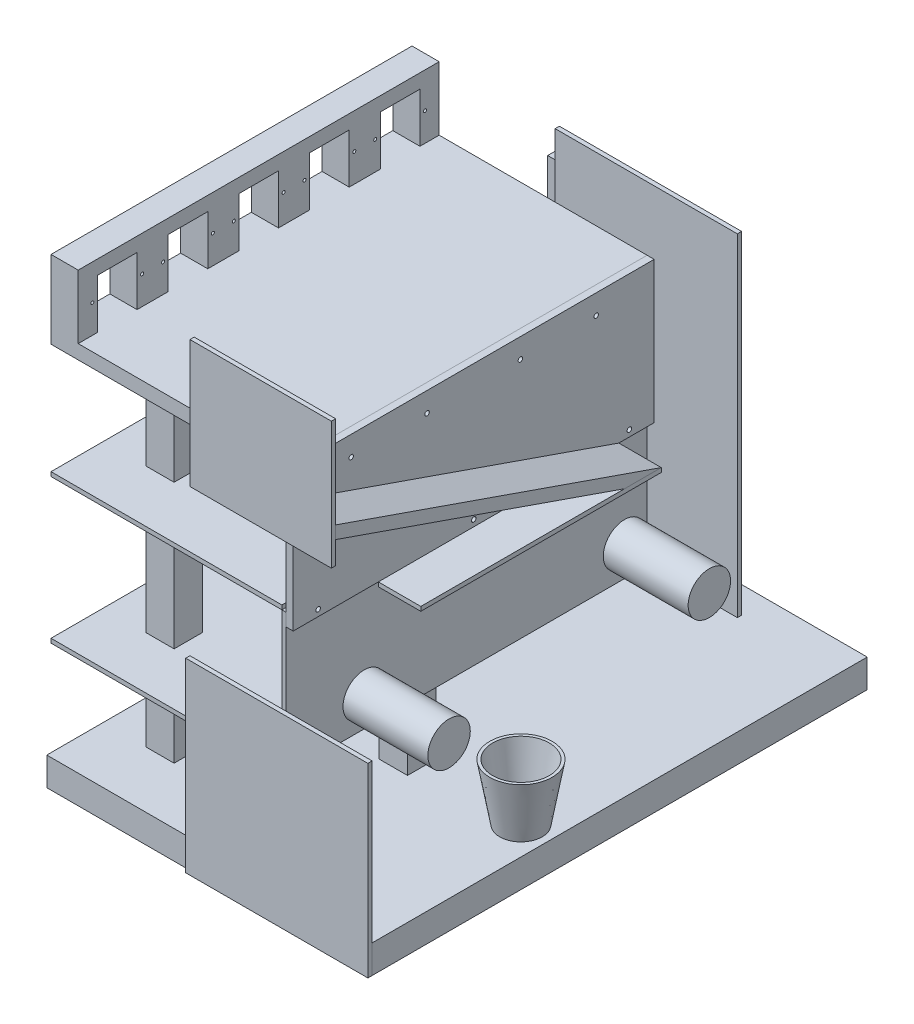
SolidWorks part; units mm, degrees
ref_plane "Front Plane" through (0, 0, 0) normal (0, 0, 1) x (1, 0, 0)
ref_plane "Top Plane" through (0, 0, 0) normal (0, 1, 0) x (1, 0, 0)
ref_plane "Right Plane" through (0, 0, 0) normal (1, 0, 0) x (0, 0, -1)
sketch "Sketch1" plane through (0, 0, 0) normal (0, 0, 1) x (1, 0, 0)
  line L0 (0, 0) -> (0, 55)
  line L1 (0, 55) -> (19.2, 55)
  line L2 (19.2, 55) -> (19.2, 10)
  line L3 (19.2, 10) -> (166.2, 10)
  line L4 (166.2, 10) -> (166.2, 0)
  line L5 (166.2, 0) -> (0, 0)
  dimension "D1" = 19.2
  dimension "D2" = 45
  dimension "D3" = 10
  dimension "D4" = 147
extrude "Boss-Extrude1" add sketch "Sketch1" along normal blind 236
sketch "Sketch2" plane through (19.2, 0, 0) normal (1, 0, 0) x (0, 0, -1)
  line L0 (-236, 10) -> (-236, 55) construction
  line L1 (-236, 10) -> (-236, 55)
  line L2 (-232.2097, 30) -> (-184.0341, 30) construction
  line L4 (-208.4, 61.6769) -> (-208.4, -8.4574) construction
  line L5 (-231.187, 27.5) -> (-166.5462, 27.5) construction
  line L6 (-236, 10) -> (0, 10) construction
  line L8 (-222.4, 45) -> (-194.4, 45)
  line L9 (-222.4, 45) -> (-222.4, 10)
  line L10 (-222.4, 10) -> (-194.4, 10)
  line L11 (-194.4, 45) -> (-194.4, 10)
  line L12 (-222.4, 45) -> (-194.4, 10) construction
  line L13 (-222.4, 10) -> (-194.4, 45) construction
  circle A0 centre (-226, 30) radius 1.075
  circle A1 centre (-190.8, 30) radius 1.075
  point P12 (-208.4, 27.5)
  dimension "D2" = 2.15
  dimension "D3" = 17.6
  dimension "D1" = 15
  dimension "D4" = 17.5
  dimension "D5" = 28
  dimension "D6" = 35
extrude "Cut-Extrude1" cut sketch "Sketch2" against normal blind 236 contours L9 L10 L11 L8 | A0 | A1
sketch "Sketch4" plane through (0, 0, 0) normal (0, 0, -1) x (-1, 0, 0)
  line L6 (-166.2, 0) -> (0, 0)
  line L7 (0, 0) -> (0, 55)
  line L8 (0, 55) -> (-19.2, 55)
  line L9 (-19.2, 55) -> (-19.2, 10)
  line L10 (-19.2, 10) -> (-166.2, 10)
  line L11 (-166.2, 10) -> (-166.2, 0)
  line L12 (-166.2, 0) -> (0, 0)
  line L13 (0, 0) -> (0, 55)
  line L14 (0, 55) -> (-19.2, 55)
  line L15 (-19.2, 55) -> (-19.2, 10)
  line L16 (-19.2, 10) -> (-166.2, 10)
  line L17 (-166.2, 10) -> (-166.2, 0)
  dimension "D1" = 0
extrude "Boss-Extrude3" add sketch "Sketch4" along normal blind 19.2
pattern_linear "LPattern2" count 5 spacing 50 along (0, 0, -1) of "Cut-Extrude1"
ref_plane "Plane8" through (0, 10, 0) normal (0, 1, 0) x (1, 0, 0)
sketch "Sketch11" plane through (0, 10, 0) normal (0, 1, 0) x (1, 0, 0)
  line L0 (166.2, -236) -> (166.2, 19.2) construction
  line L1 (166.2, -236) -> (166.2, 19.2)
  line L2 (166.2, 19.2) -> (171.2, 19.2)
  line L3 (171.2, 19.2) -> (171.2, -236)
  line L4 (171.2, -236) -> (166.2, -236)
  dimension "D1" = 5
extrude "Boss-Extrude6" add sketch "Sketch11" against normal blind 100 separate body
sketch "Sketch12" plane through (0, 0, 0) normal (0, -1, 0) x (1, 0, 0)
  line L0 (166.2, 236) -> (166.2, -19.2) construction
  line L1 (166.2, 24.8) -> (166.2, 18.8)
  line L2 (193.3393, 108.4) -> (-22.8673, 108.4) construction
  line L3 (166.2, 24.8) -> (163.2, 24.8)
  line L4 (163.2, 24.8) -> (163.2, 18.8)
  line L5 (163.2, 18.8) -> (166.2, 18.8)
  line L6 (166.2, 192) -> (163.2, 192)
  line L7 (166.2, -19.2) -> (0, -19.2) construction
  line L8 (163.2, 192) -> (163.2, 198)
  line L9 (163.2, 198) -> (166.2, 198)
  line L10 (166.2, 192) -> (166.2, 198)
  line L11 (166.2, 78.4) -> (163.2, 78.4)
  line L12 (163.2, 78.4) -> (163.2, 72.4)
  line L13 (163.2, 72.4) -> (166.2, 72.4)
  line L14 (166.2, -19.2) -> (166.2, 236) construction
  line L15 (166.2, 72.4) -> (166.2, 78.4)
  line L16 (163.2, 144.4) -> (166.2, 144.4)
  line L17 (163.2, 138.4) -> (163.2, 144.4)
  line L18 (166.2, 138.4) -> (163.2, 138.4)
  line L19 (166.2, 144.4) -> (166.2, 138.4)
  dimension "D1" = 3
  dimension "D2" = 6
  dimension "D3" = 38
  dimension "D4" = 3
  dimension "D5" = 6
  dimension "D6" = 30
extrude "Boss-Extrude7" add sketch "Sketch12" along normal blind 8
ref_plane "Plane13" through (0, 0, 108.4) normal (0, 0, 1) x (1, 0, 0)
sketch "Sketch13" plane through (163.2, 0, 0) normal (-1, 0, 0) x (0, 0, 1)
  line L0 (75.4, -8) -> (75.4, 0) construction
  line L1 (72.4, -4) -> (78.4, -4) construction
  circle A0 centre (75.4, -4) radius 1.6
extrude "Cut-Extrude2" cut sketch "Sketch13" against normal blind 70
mirror "Mirror1" about plane through (0, 0, 108.4) normal (0, 0, 1) of "Cut-Extrude2"
sketch "Sketch14" plane through (163.2, 0, 0) normal (-1, 0, 0) x (0, 0, 1)
  line L0 (21.8, -8.505) -> (21.8, 0.2869) construction
  line L1 (18.8, -4) -> (24.8, -4) construction
  circle A0 centre (21.8, -4) radius 1.6
extrude "Cut-Extrude4" cut sketch "Sketch14" against normal blind 70
mirror "Mirror2" about plane through (0, 0, 108.4) normal (0, 0, 1) of "Cut-Extrude4"
sketch "Sketch15" plane through (171.2, 0, 0) normal (1, 0, 0) x (0, 0, -1)
  line L0 (-5.8, -90) -> (-236, -10)
  line L1 (-236, -10) -> (-236, -19)
  line L2 (-236, -19) -> (-31.6975, -90)
  line L3 (-31.6975, -90) -> (-5.8, -90)
  line L4 (19.2, 10) -> (-236, 10)
  line L5 (-236, 10) -> (-236, -90)
  line L6 (-236, -90) -> (19.2, -90)
  line L7 (19.2, -90) -> (19.2, 10)
  line L9 (-236, -10) -> (-236, -19)
  line L10 (-31.6975, -90) -> (19.2, -90)
  line M14 (-236, 10) -> (-236, -90)
  line M15 (-236, -90) -> (19.2, -90)
  dimension "D2" = 25
  dimension "D3" = 20
  dimension "D4" = 9
  dimension "D1" = 0
extrude "Boss-Extrude8" add sketch "Sketch15" along normal blind 30 contours L2 L0 M14 M15
sketch "Sketch16" plane through (0, 0, 236) normal (0, 0, 1) x (1, 0, 0)
  line L0 (0, 55) -> (201.2, 55)
  line L1 (201.2, -90) -> (201.2, 55)
  line L2 (0, 55) -> (0, -90)
  line L3 (0, -90) -> (201.2, -90)
extrude "Boss-Extrude9" add sketch "Sketch16" along normal blind 3 separate body
mirror "Mirror3" about plane through (0, 0, 108.4) normal (0, 0, 1) of bodies 124
sketch "Sketch17" plane through (0, 0, 239) normal (0, 0, 1) x (1, 0, 0)
  line L0 (166.2, 0) -> (0, 0) construction
  line L1 (166.2, 0) -> (19.2, 0)
  line L2 (166.2, 10) -> (19.2, 10) construction
  line L3 (166.2, 10) -> (19.2, 10)
  line L4 (19.2, 10) -> (19.2, 0)
  line L5 (166.2, 10) -> (166.2, 0)
  line L6 (19.2, 5) -> (166.2, 5) construction
  line L7 (92.7, 20.9374) -> (92.7, -18.0849) construction
  circle A0 centre (42.9728, 5) radius 1.6
  circle A1 centre (142.4272, 5) radius 1.6
  circle A2 centre (92.7, 5) radius 1.6
  dimension "D1" = 49.7272
sketch "Sketch18" plane through (166.2, 0, 0) normal (-1, 0, 0) x (0, 0, 1)
  line L1 (-19.2, -90) -> (236, -90) construction
  line L4 (-19.2, -81) -> (236, -81)
  line L6 (-19.2, -81) -> (-19.2, -180)
  line L7 (-19.2, -180) -> (236, -180)
  line L8 (236, -180) -> (236, -81)
  dimension "D1" = 255.2
  dimension "D2" = 99
  dimension "D3" = 9
extrude "Boss-Extrude12" add sketch "Sketch18" along normal blind 3 separate body
sketch "Sketch19" plane through (163.2, 0, 0) normal (-1, 0, 0) x (0, 0, 1)
  line L6 (-43.8687, -85.5) -> (229.5444, -85.5) construction
  line L7 (108.3445, -58.3999) -> (108.3445, -107.1736) construction
  circle A0 centre (-1.6555, -85.5) radius 1.6
  circle A1 centre (218.3445, -85.5) radius 1.6
  circle A2 centre (108.3445, -85.5) radius 1.6
  dimension "D1" = 110
extrude "Cut-Extrude5" cut sketch "Sketch19" against normal up to surface (8 mm away)
sketch "Sketch21" plane through (166.2, 0, 0) normal (1, 0, 0) x (0, 0, -1)
  line L0 (-31.6975, -90) -> (-5.8, -90) construction
  line L1 (-5.8, -90) -> (19.2, -90) construction
  line L2 (-236, -90) -> (-31.6975, -90) construction
  line L3 (-31.6975, -90) -> (-5.8, -90)
  line L4 (-236, -180) -> (19.2, -180)
  line L5 (19.2, -180) -> (19.2, -81)
  line L6 (19.2, -81) -> (-236, -81)
  line L7 (-236, -81) -> (-236, -180)
  line L8 (-236, -180) -> (19.2, -180)
  line L9 (19.2, -180) -> (19.2, -90)
  line L11 (-236, -90) -> (-236, -180)
  line L12 (-5.8, -90) -> (19.2, -90)
  line L13 (-236, -90) -> (-31.6975, -90)
  dimension "D1" = 0
sketch "Sketch27" plane through (166.2, 0, 0) normal (1, 0, 0) x (0, 0, -1)
  line L0 (-243.634, -158.85) -> (44.8796, -158.85) construction
  line L1 (-180.8, -121.996) -> (-180.8, -209.99) construction
  line L2 (3.2, -131.3287) -> (3.2, -198.7908) construction
  line L4 (-236, -180) -> (19.2, -180)
  line L5 (19.2, -180) -> (19.2, -81)
  line L6 (19.2, -81) -> (-236, -81)
  line L7 (-236, -81) -> (-236, -180)
  line L8 (-236, -180) -> (19.2, -180)
  line L9 (19.2, -180) -> (19.2, -81)
  line L10 (19.2, -81) -> (-236, -81)
  line L11 (-236, -81) -> (-236, -180)
  circle A0 centre (-180.8, -158.85) radius 11.05
  circle A1 centre (3.2, -158.85) radius 1.6
  dimension "D4" = 16
  dimension "D2" = 21.15
  dimension "D3" = 200
  dimension "D1" = 0
extrude "Cut-Extrude9" cut sketch "Sketch27" against normal blind 103 contours A1 | A0
sketch "Sketch28" plane through (166.2, 0, 0) normal (1, 0, 0) x (0, 0, -1)
  circle A4 centre (-180.8, -158.85) radius 15
  circle A5 centre (3.2, -158.85) radius 15
extrude "Boss-Extrude14" add sketch "Sketch28" along normal blind 60 separate body
sketch "Sketch29" plane through (0, -180, 0) normal (0, -1, 0) x (1, 0, 0)
  line L0 (0, 239) -> (230, 239)
  line L1 (230, 239) -> (230, -111)
  line L2 (230, -111) -> (0, -111)
  line L3 (0, -111) -> (0, 239)
  dimension "D1" = 230
  dimension "D2" = 350
extrude "Boss-Extrude15" add sketch "Sketch29" along normal blind 20 from offset 70 separate body
sketch "Sketch30" plane through (0, 0, 0) normal (0, -1, 0) x (1, 0, 0)
  line L0 (0, 239) -> (0, -111) construction
  line L1 (0, 239) -> (0, -111)
  line L2 (40, 250.1011) -> (40, -40.4223) construction
  line L3 (230, 239) -> (0, 239) construction
  line L4 (230, 239) -> (0, 239)
  line L5 (0, -111) -> (230, -111) construction
  line L6 (0, -111) -> (230, -111)
  line L7 (-47.8894, 189) -> (304.6658, 189) construction
  line L8 (-15.7578, 39) -> (291.2776, 39) construction
  line L10 (30, 199) -> (50, 199)
  line L11 (30, 199) -> (30, 179)
  line L12 (30, 179) -> (50, 179)
  line L13 (50, 199) -> (50, 179)
  line L14 (30, 199) -> (50, 179) construction
  line L15 (30, 179) -> (50, 199) construction
  line L16 (30, 49) -> (50, 49)
  line L17 (30, 49) -> (30, 29)
  line L18 (30, 29) -> (50, 29)
  line L19 (50, 49) -> (50, 29)
  line L20 (30, 49) -> (50, 29) construction
  line L21 (30, 29) -> (50, 49) construction
  line L22 (-28.8064, 114) -> (348.0208, 114) construction
  line L24 (120, 124) -> (140, 124)
  line L25 (120, 124) -> (120, 104)
  line L26 (120, 104) -> (140, 104)
  line L27 (140, 124) -> (140, 104)
  line L28 (120, 124) -> (140, 104) construction
  line L29 (120, 104) -> (140, 124) construction
  point P10 (40, 189)
  point P15 (40, 39)
  point P22 (130, 114)
  point P27 (40, 104.8394)
  dimension "D1" = 40
  dimension "D2" = 150
  dimension "D3" = 50
  dimension "D4" = 20
  dimension "D5" = 75
  dimension "D6" = 90
extrude "Boss-Extrude17" add sketch "Sketch30" along normal up to surface (250 mm away) separate body contours L19 L16 L17 L18 | L13 L10 L11 L12 | L25 L24 L27 L26 up to face at (115, -250, 64)
sketch "Sketch31" plane through (0, 0, 239) normal (0, 0, 1) x (1, 0, 0)
  line L0 (101.2, 55) -> (101.2, -35)
  line L1 (101.2, -35) -> (201.2, -35)
  line L4 (0, 55) -> (0, -90)
  line L5 (0, -90) -> (201.2, -90)
  line L6 (201.2, -90) -> (201.2, 55)
  line L7 (201.2, 55) -> (0, 55)
  line L8 (0, 55) -> (0, -90)
  line L9 (0, -90) -> (201.2, -90)
  line L10 (201.2, -90) -> (201.2, -35)
  line L11 (101.2, 55) -> (0, 55)
  dimension "D2" = 100
  dimension "D3" = 90
  dimension "D1" = 0
extrude "Cut-Extrude10" cut sketch "Sketch31" against normal up to surface (3 mm away) up to face at (100.6, -17.5, 236)
sketch "Sketch33" plane through (0, 0, -22.2) normal (0, 0, -1) x (-1, 0, 0)
  line L4 (0, -90) -> (0, 55)
  line L5 (0, 55) -> (-201.2, 55)
  line L6 (-201.2, 55) -> (-201.2, -90)
  line L7 (-201.2, -90) -> (0, -90)
  line L8 (0, -90) -> (0, 55)
  line L9 (0, 55) -> (-201.2, 55)
  line L10 (-201.2, 55) -> (-201.2, -90)
  line L11 (-201.2, -90) -> (0, -90)
  dimension "D1" = 0
extrude "Cut-Extrude11" cut sketch "Sketch33" against normal up to surface (3 mm away) up to face at (100.6, -17.5, -19.2)
sketch "Sketch34" plane through (0, 0, -19.2) normal (0, 0, -1) x (-1, 0, 0)
  line L0 (-230, -180) -> (-230, 55)
  line L1 (-230, 55) -> (-101.2, 55)
  line L2 (-101.2, 55) -> (-101.2, -180)
  line L3 (-166.2, -180) -> (-230, -180)
  line L4 (-101.2, -180) -> (-163.2, -180)
  line L6 (-166.2, -180) -> (-163.2, -180)
extrude "Boss-Extrude18" add sketch "Sketch34" along normal blind 3 separate body
sketch "Sketch36" plane through (0, -250, 0) normal (0, 1, 0) x (1, 0, 0)
  line L0 (230, -239) -> (0, -239) construction
  circle A0 centre (210.207, -114) radius 15
  dimension "D1" = 125
extrude "Boss-Extrude19" add sketch "Sketch36" along normal blind 40 draft 10 separate body draft outward yes
shell "Shell1" thickness 2
sketch "Sketch45" plane through (0, 0, 239) normal (0, 0, 1) x (1, 0, 0)
  line L0 (230, -270) -> (230, -138.5898)
  line L1 (230, -138.5898) -> (101.2, -138.5898)
  line L2 (101.2, -180) -> (101.2, 55) construction
  line L3 (101.2, -138.5898) -> (101.2, -270)
  line L4 (230, -270) -> (0, -270) construction
  line L5 (101.2, -270) -> (230, -270)
extrude "Boss-Extrude20" add sketch "Sketch45" along normal blind 3 separate body
sketch "Sketch46" plane through (0, -250, 0) normal (0, 1, 0) x (1, 0, 0)
  line L1 (60, 75.1) -> (80, 75.1)
  line L2 (60, 75.1) -> (60, 55.1)
  line L3 (60, 55.1) -> (80, 55.1)
  line L4 (80, 75.1) -> (80, 55.1)
  line L5 (60, 75.1) -> (80, 55.1) construction
  line L6 (60, 55.1) -> (80, 75.1) construction
  line L8 (-58.4832, 65.1) -> (331.0129, 65.1) construction
  line L9 (0, 111) -> (230, 111) construction
  line L10 (0, -239) -> (0, 111) construction
  point P0 (70, 65.1)
  dimension "D1" = 20
  dimension "D2" = 45.9
  dimension "D3" = 60
extrude "Boss-Extrude21" add sketch "Sketch46" along normal up to surface (250 mm away) separate body up to face at (148.38, 0, 108.4)
sketch "Sketch47" plane through (80, 0, 0) normal (1, 0, 0) x (0, 0, -1)
  line L1 (55.1, -20) -> (75.1, -20)
  line L2 (55.1, 0) -> (55.1, -250) construction
  line L3 (75.1, 0) -> (75.1, -250) construction
  line L4 (55.1, 0) -> (75.1, 0) construction
  line L5 (55.1, -20) -> (55.1, 0)
  line L6 (55.1, 0) -> (75.1, 0)
  line L7 (75.1, 0) -> (75.1, -20)
  dimension "D1" = 20
extrude "Boss-Extrude22" add sketch "Sketch47" along normal blind 50
sketch "Sketch48" plane through (0, 0, 0) normal (0, 1, 0) x (1, 0, 0)
  line L0 (14.0463, 65.1) -> (168.5602, 65.1) construction
  line L1 (130, 75.1) -> (130, 55.1) construction
  circle A0 centre (115, 65.1) radius 30
  dimension "D1" = 60
  dimension "D2" = 15
extrude "Boss-Extrude23" add sketch "Sketch48" against normal blind 180 draft 3 from offset 20 separate body offset against normal yes
shell "Shell2" thickness 2
sketch "Sketch49" plane through (0, -90, 0) normal (0, -1, 0) x (1, 0, 0)
  line L2 (201.2, 175.8) -> (171.2, 175.8)
  line L4 (171.2, 175.8) -> (171.2, 5.8)
  line L5 (201.2, 5.8) -> (201.2, 175.8)
  line L6 (171.2, 5.8) -> (201.2, 5.8)
  dimension "D1" = 170
extrude "Boss-Extrude24" add sketch "Sketch49" along normal blind 3 separate body
sketch "Sketch50" plane through (0, -180, 0) normal (0, -1, 0) x (1, 0, 0)
  line L0 (50, 179) -> (50, 199) construction
  line L1 (50, 199) -> (30, 199) construction
  line L2 (30, 199) -> (30, 179) construction
  line L3 (30, 179) -> (50, 179) construction
  line L4 (140, 104) -> (140, 124) construction
  line L5 (140, 124) -> (120, 124) construction
  line L6 (120, 124) -> (120, 104) construction
  line L7 (120, 104) -> (140, 104) construction
  line L8 (50, 29) -> (50, 49) construction
  line L9 (50, 49) -> (30, 49) construction
  line L10 (30, 49) -> (30, 29) construction
  line L11 (30, 29) -> (50, 29) construction
  line L12 (30, 29) -> (30, 49) construction
  line L13 (50, 29) -> (30, 29) construction
  line L14 (166.2, -19.2) -> (0, -19.2) construction
  line L15 (0, 236) -> (0, -19.2) construction
  line L16 (0, 236) -> (166.2, 236) construction
  line L17 (166.2, -19.2) -> (166.2, 236) construction
  line L18 (50, 179) -> (50, 199)
  line L19 (50, 199) -> (30, 199)
  line L20 (30, 199) -> (30, 179)
  line L21 (30, 179) -> (50, 179)
  line L22 (140, 104) -> (140, 124)
  line L23 (140, 124) -> (120, 124)
  line L24 (120, 124) -> (120, 104)
  line L25 (120, 104) -> (140, 104)
  line L26 (50, 29) -> (50, 49)
  line L27 (50, 49) -> (30, 49)
  line L28 (30, 49) -> (30, 29)
  line L29 (30, 29) -> (50, 29)
  line L30 (30, 29) -> (30, 49)
  line L31 (50, 29) -> (30, 29)
  line L32 (166.2, -19.2) -> (0, -19.2)
  line L33 (0, 236) -> (0, -19.2)
  line L34 (0, 236) -> (166.2, 236)
  line L35 (166.2, -19.2) -> (166.2, 236)
  line M3 (163.2, 236) -> (163.2, -19.2)
extrude "Boss-Extrude25" add sketch "Sketch50" along normal blind 3 separate body contours L34 L33 L32 L29 L28 L27 L26 L25 L24 L23 L22 L21 L20 L19 L18 M3
sketch "Sketch51" plane through (0, -81, 0) normal (0, 1, 0) x (1, 0, 0)
  line L0 (140, -104) -> (120, -104) construction
  line L1 (120, -104) -> (120, -124) construction
  line L2 (120, -124) -> (140, -124) construction
  line L3 (140, -124) -> (140, -104) construction
  line L4 (50, -49) -> (50, -29) construction
  line L5 (50, -29) -> (30, -29) construction
  line L6 (30, -29) -> (30, -49) construction
  line L7 (30, -49) -> (50, -49) construction
  line L8 (50, -199) -> (50, -179) construction
  line L9 (50, -179) -> (30, -179) construction
  line L10 (30, -179) -> (30, -199) construction
  line L11 (30, -199) -> (50, -199) construction
  line L12 (0, -236) -> (163.2, -236) construction
  line L13 (0, -236) -> (0, 19.2) construction
  line L14 (163.2, 19.2) -> (0, 19.2) construction
  line L15 (166.2, -236) -> (166.2, 19.2) construction
  line L16 (140, -104) -> (120, -104)
  line L17 (120, -104) -> (120, -124)
  line L18 (120, -124) -> (140, -124)
  line L19 (140, -124) -> (140, -104)
  line L20 (50, -49) -> (50, -29)
  line L21 (50, -29) -> (30, -29)
  line L22 (30, -29) -> (30, -49)
  line L23 (30, -49) -> (50, -49)
  line L24 (50, -199) -> (50, -179)
  line L25 (50, -179) -> (30, -179)
  line L26 (30, -179) -> (30, -199)
  line L27 (30, -199) -> (50, -199)
  line L28 (0, -236) -> (163.2, -236)
  line L29 (0, -236) -> (0, 19.2)
  line L30 (163.2, 19.2) -> (0, 19.2)
  line L31 (166.2, -236) -> (166.2, 19.2)
  line M3 (163.2, 19.2) -> (163.2, -236)
extrude "Boss-Extrude27" add sketch "Sketch51" along normal blind 3 separate body contours L30 L29 L28 L19 L18 L17 L16 L23 L22 L21 L20 L27 L26 L25 L24 M3
